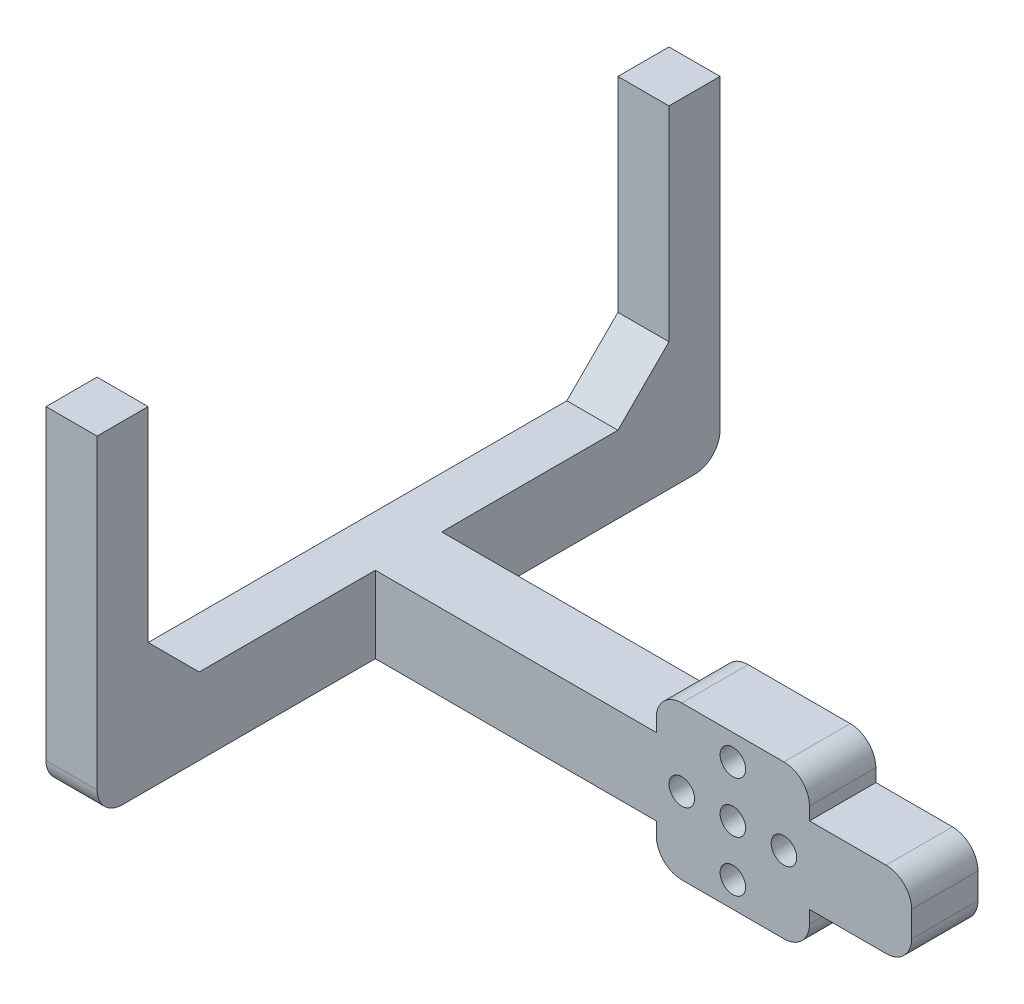
SolidWorks part; units mm, degrees
ref_plane "Front Plane" through (0, 0, 0) normal (0, 0, 1) x (1, 0, 0)
ref_plane "Top Plane" through (0, 0, 0) normal (0, 1, 0) x (1, 0, 0)
ref_plane "Right Plane" through (0, 0, 0) normal (1, 0, 0) x (0, 0, -1)
sketch "Sketch1" plane through (0, 0, 0) normal (1, 0, 0) x (0, 0, -1)
  line L1 (-6.5, -7.5) -> (6.5, -7.5)
  line L2 (-6.5, -7.5) -> (-6.5, 7.5)
  line L3 (-6.5, 7.5) -> (6.5, 7.5)
  line L4 (6.5, -7.5) -> (6.5, 7.5)
  line L5 (-6.5, -7.5) -> (6.5, 7.5) construction
  line L6 (-6.5, 7.5) -> (6.5, -7.5) construction
  point P0 (0, 0)
  dimension "D1" = 13
  dimension "D2" = 15
extrude "Boss-Extrude1" add sketch "Sketch1" along normal blind 150
sketch "Sketch5" plane through (0, 0, 6.5) normal (0, 0, 1) x (1, 0, 0)
  line L0 (115, 7.5) -> (115, -7.5)
  line L1 (150, 7.5) -> (0, 7.5) construction
  line L2 (150, -7.5) -> (0, -7.5) construction
  line L4 (0, 7.5) -> (0, -7.5) construction
  circle A0 centre (115, 0) radius 2.5
  circle A1 centre (125, 0) radius 2.5
  circle A2 centre (105, 0) radius 2.5
  dimension "D1" = 5
  dimension "D3" = 10
  dimension "D4" = 10
  dimension "D5" = 5
  dimension "D6" = 5
  dimension "D2" = 115
extrude "Cut-Extrude3" cut sketch "Sketch5" against normal through all contours A2 | A0 | A1
sketch "Sketch8" plane through (0, 0, 0) normal (-1, 0, 0) x (0, 0, 1)
  line L1 (-6.5, 7.5) -> (6.5, 7.5)
  line L2 (-6.5, 7.5) -> (-6.5, -7.5)
  line L3 (-6.5, -7.5) -> (6.5, -7.5)
  line L4 (6.5, 7.5) -> (6.5, -7.5)
extrude "Boss-Extrude3" add sketch "Sketch8" along normal blind 15
sketch "Sketch10" plane through (0, -7.5, 0) normal (0, -1, 0) x (-1, 0, 0)
  line L0 (-150, -6.5) -> (15, -6.5) construction
  line L1 (15, 6.5) -> (-15, 6.5)
  line L2 (15, 6.5) -> (15, -6.5)
  line L3 (15, -6.5) -> (-15, -6.5)
  line L4 (-15, 6.5) -> (-15, -6.5)
  line L5 (15, 6.5) -> (-15, -6.5) construction
  line L6 (15, -6.5) -> (-15, 6.5) construction
  line L7 (15, 6.5) -> (15, -6.5) construction
  line L8 (15, 0) -> (-15, 0)
  circle A0 centre (7, 0) radius 1.6
  circle A1 centre (-12, 0) radius 1.6
  point P0 (0, 0)
  dimension "D3" = 3.2
  dimension "D4" = 3.2
  dimension "D5" = 8
  dimension "D6" = 3
  dimension "D1" = 15
  dimension "D2" = 30
extrude "Cut-Extrude4" cut sketch "Sketch10" against normal through all contours A0 | A1
sketch "Sketch11" plane through (0, 0, -6.5) normal (0, 0, -1) x (-1, 0, 0)
  line L1 (-130, -15) -> (-100, -15)
  line L2 (-130, -15) -> (-130, 15)
  line L3 (-130, 15) -> (-100, 15)
  line L4 (-100, -15) -> (-100, 15)
  line L5 (-130, -15) -> (-100, 15) construction
  line L6 (-130, 15) -> (-100, -15) construction
  point P0 (-115, 0)
  dimension "D1" = 30
  dimension "D2" = 30
extrude "Boss-Extrude4" add sketch "Sketch11" against normal blind 13
sketch "Sketch12" plane through (0, 0, -6.5) normal (0, 0, -1) x (-1, 0, 0)
  line L0 (-115, 7.5) -> (-115, -7.5) construction
  line L1 (-115, 7.5) -> (-115, -7.5)
  circle A0 centre (-115, 10) radius 2.5
  circle A1 centre (-105, 0) radius 2.5
  circle A2 centre (-105, 0) radius 2.5
  circle A3 centre (-125, 0) radius 2.5
  circle A4 centre (-125, 0) radius 2.5
  circle A5 centre (-115, 0) radius 2.5
  circle A6 centre (-115, 0) radius 2.5
  circle A7 centre (-115, -10) radius 2.5
  dimension "D4" = 10
  dimension "D5" = 10
  dimension "D6" = 5
  dimension "D7" = 5
  dimension "D1" = 0
  dimension "D2" = 0
  dimension "D3" = 0
extrude "Cut-Extrude5" cut sketch "Sketch12" against normal through all contours A0 | A4 | A6 | A2 | A7
fillet "Fillet1" radius 5 4 edges at (130, -15, 0) (100, -15, 0) (100, 15, 0) (130, 15, 0)
fillet "Fillet2" radius 5 2 edges at (150, -7.5, 0) (150, 7.5, 0)
sketch "Sketch13" plane through (0, 7.5, 0) normal (0, 1, 0) x (1, 0, 0)
  circle A1 centre (2.5, 0) radius 3
  circle A2 centre (-7, 0) radius 1.6 construction
  dimension "D1" = 6
  dimension "D2" = 9.5
extrude "Cut-Extrude6" cut sketch "Sketch13" against normal through all
sketch "Sketch14" plane through (150, 0, 0) normal (1, 0, 0) x (0, 0, -1)
  line L0 (-6.5, 2.5) -> (-6.5, -2.5) construction
  line L1 (6.5, -2.5) -> (6.5, 2.5) construction
  circle A0 centre (0, 0) radius 3
  dimension "D1" = 6
  dimension "D2" = 6.5
  dimension "D3" = 6.5
extrude "Cut-Extrude7" [suppressed] cut sketch "Sketch14" against normal blind 150
sketch "Sketch15" plane through (-15, 0, 0) normal (-1, 0, 0) x (0, 0, 1)
  line L1 (-6.5, 7.5) -> (6.5, 7.5)
  line L2 (-6.5, 7.5) -> (-6.5, -7.5)
  line L3 (-6.5, -7.5) -> (6.5, -7.5)
  line L4 (6.5, 7.5) -> (6.5, -7.5)
extrude "Boss-Extrude5" add sketch "Sketch15" along normal blind 40
sketch "Sketch23" plane through (0, 0, 6.5) normal (0, 0, 1) x (1, 0, 0)
  line L0 (100, -7.5) -> (-55, -7.5) construction
  line L1 (35, -7.5) -> (45, -7.5)
  line L2 (35, -7.5) -> (35, 7.5)
  line L3 (35, 7.5) -> (45, 7.5)
  line L4 (45, -7.5) -> (45, 7.5)
  line L5 (100, 7.5) -> (-55, 7.5) construction
  circle A0 centre (105, 0) radius 2.5 construction
  dimension "D1" = 10
  dimension "D2" = 60
extrude "Boss-Extrude10" add sketch "Sketch23" along normal blind 54.49
sketch "Sketch24" plane through (0, 0, -6.5) normal (0, 0, -1) x (-1, 0, 0)
  line L4 (-45, -7.5) -> (-35, -7.5)
  line L5 (-45, 7.5) -> (-45, -7.5)
  line L6 (-35, 7.5) -> (-45, 7.5)
  line L7 (-35, -7.5) -> (-35, 7.5)
  line L8 (-45, -7.5) -> (-35, -7.5)
  line L9 (-45, 7.5) -> (-45, -7.5)
  line L10 (-35, 7.5) -> (-45, 7.5)
  line L11 (-35, -7.5) -> (-35, 7.5)
  dimension "D1" = 0
extrude "Boss-Extrude11" add sketch "Sketch24" along normal blind 54.49
sketch "Sketch25" plane through (0, -7.5, 0) normal (0, -1, 0) x (-1, 0, 0)
  circle A0 centre (-40, 57.2755) radius 1.6
  circle A1 centre (-40, -57.2755) radius 1.6
extrude "Cut-Extrude14" [suppressed] cut sketch "Sketch25" against normal blind 50
sketch "Sketch26" plane through (0, -7.5, 0) normal (0, -1, 0) x (1, 0, 0)
  line L0 (45, 60.99) -> (45, 6.5) construction
  line L1 (35, 60.99) -> (45, 60.99)
  line L2 (35, 60.99) -> (35, 50.99)
  line L3 (35, 50.99) -> (45, 50.99)
  line L4 (45, 60.99) -> (45, 50.99)
  line L5 (35, -60.99) -> (35, -6.5) construction
  line L6 (45, -60.99) -> (35, -60.99)
  line L7 (45, -60.99) -> (45, -50.99)
  line L8 (45, -50.99) -> (35, -50.99)
  line L9 (35, -60.99) -> (35, -50.99)
  dimension "D1" = 10
  dimension "D2" = 10
extrude "Boss-Extrude12" [suppressed] add sketch "Sketch26" along normal blind 50
sketch "Sketch27" plane through (0, 7.5, 0) normal (0, 1, 0) x (1, 0, 0)
  line L4 (45, 60.99) -> (35, 60.99)
  line L5 (35, 60.99) -> (35, 50.99)
  line L6 (35, 50.99) -> (45, 50.99)
  line L7 (45, 50.99) -> (45, 60.99)
  line L8 (45, 60.99) -> (35, 60.99)
  line L9 (35, 60.99) -> (35, 50.99)
  line L10 (35, 50.99) -> (45, 50.99)
  line L11 (45, 50.99) -> (45, 60.99)
  line L12 (35, -60.99) -> (45, -60.99)
  line L13 (45, -60.99) -> (45, -50.99)
  line L14 (45, -50.99) -> (35, -50.99)
  line L15 (35, -50.99) -> (35, -60.99)
  line L16 (35, -60.99) -> (45, -60.99)
  line L17 (45, -60.99) -> (45, -50.99)
  line L18 (45, -50.99) -> (35, -50.99)
  line L19 (35, -50.99) -> (35, -60.99)
  dimension "D1" = 0
  dimension "D2" = 0
extrude "Boss-Extrude13" add sketch "Sketch27" along normal blind 50
sketch "Sketch28" plane through (0, -7.5, 0) normal (0, -1, 0) x (1, 0, 0)
  line L1 (-55, 6.5) -> (35, 6.5)
  line L2 (-55, 6.5) -> (-55, -6.5)
  line L3 (-55, -6.5) -> (35, -6.5)
  line L4 (35, 6.5) -> (35, -6.5)
extrude "Cut-Extrude15" cut sketch "Sketch28" against normal through all
chamfer "Chamfer1" distance 10 angle 45 2 edges at (40, 7.5, -50.99) (40, 7.5, 50.99)
fillet "Fillet3" radius 5 2 edges at (40, -7.5, -60.99) (40, -7.5, 60.99)
